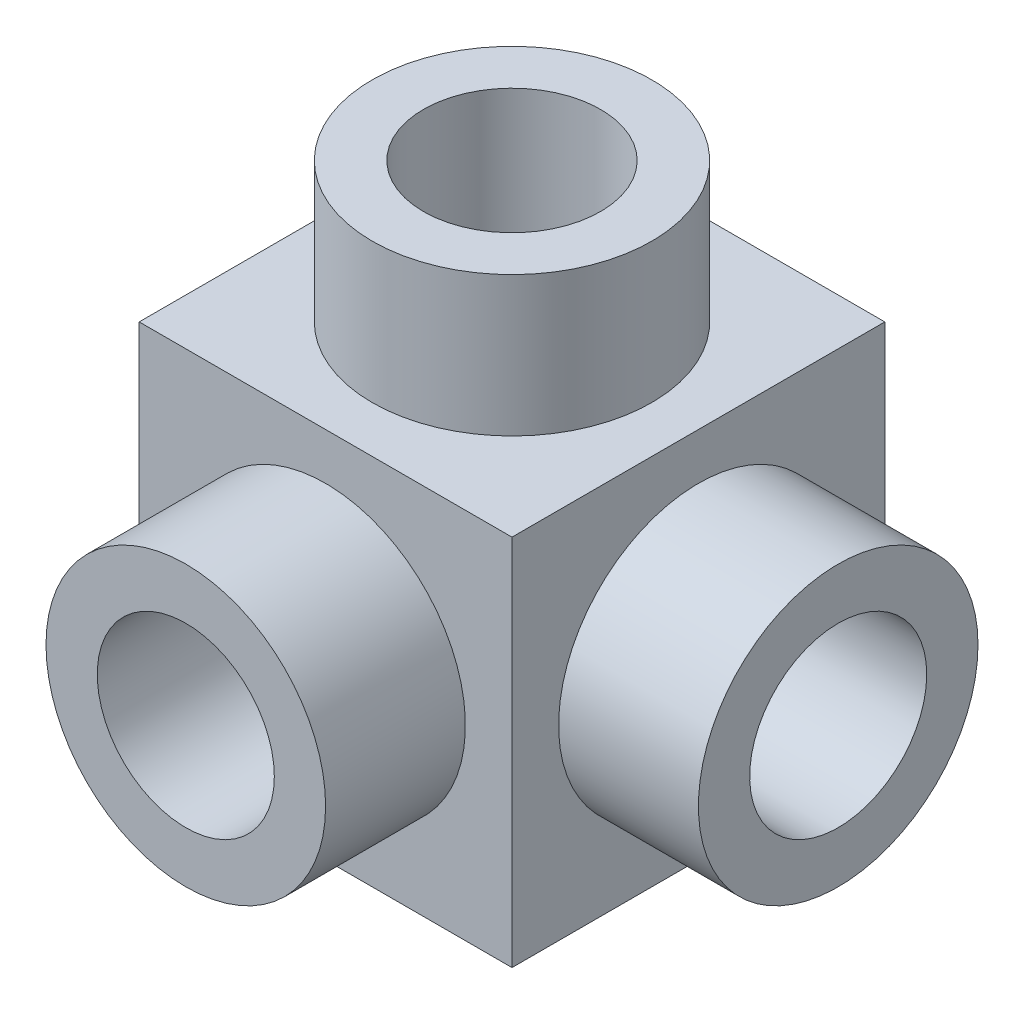
SolidWorks part; units mm, degrees
ref_plane "Alzado" through (0, 0, 0) normal (0, 0, 1) x (1, 0, 0)
ref_plane "Planta" through (0, 0, 0) normal (0, 1, 0) x (1, 0, 0)
ref_plane "Vista lateral" through (0, 0, 0) normal (1, 0, 0) x (0, 0, -1)
sketch "Croquis1" plane through (0, 0, 0) normal (0, 0, 1) x (1, 0, 0)
  circle A1 centre (0, 0) radius 19
  circle A2 centre (0, 0) radius 30
extrude "Saliente-Extruir1" add sketch "Croquis1" along normal blind 30
sketch "Croquis2" plane through (0, 0, 0) normal (0, 0, 1) x (1, 0, 0)
  line L1 (40, 40) -> (-40, 40)
  line L2 (40, 40) -> (40, -40)
  line L3 (40, -40) -> (-40, -40)
  line L4 (-40, 40) -> (-40, -40)
  point P0 (0, 0)
extrude "Saliente-Extruir2" add sketch "Croquis2" against normal blind 80
ref_plane "Plano1" through (40, 0, 0) normal (1, 0, 0) x (0, 0, -1)
sketch "Croquis3" plane through (40, 0, 0) normal (1, 0, 0) x (0, 0, -1)
  line L0 (0, 40) -> (0, -40) construction
  line L1 (0, -40) -> (80, -40) construction
  circle A0 centre (40, 0) radius 19
  circle A1 centre (40, 0) radius 30
extrude "Saliente-Extruir3" add sketch "Croquis3" along normal blind 30
ref_plane "Plano2" through (0, 40, 0) normal (0, 1, 0) x (1, 0, 0)
sketch "Croquis4" plane through (0, 40, 0) normal (0, 1, 0) x (1, 0, 0)
  circle A0 centre (0, 40) radius 19
  circle A1 centre (0, 40) radius 30
extrude "Saliente-Extruir4" add sketch "Croquis4" along normal blind 30
